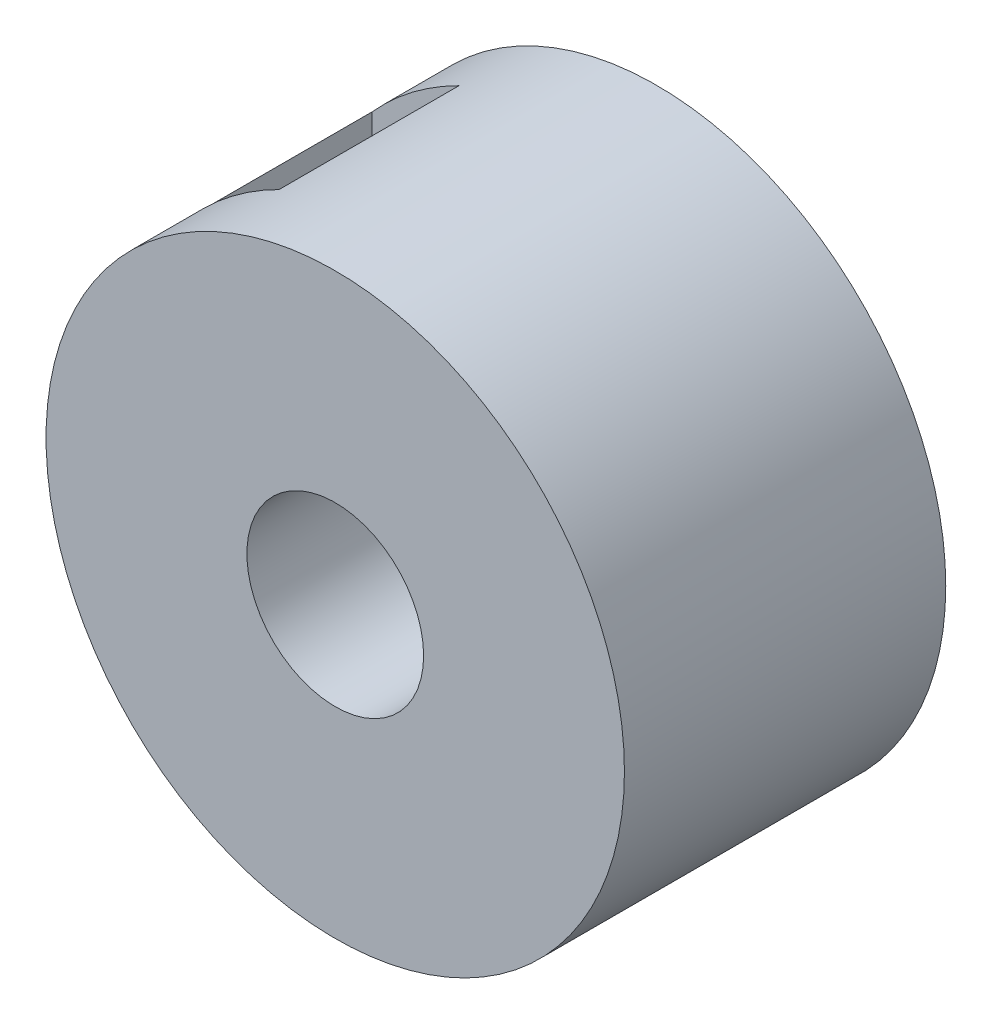
SolidWorks part; units mm, degrees
ref_plane "Front Plane" through (0, 0, 0) normal (0, 0, 1) x (1, 0, 0)
ref_plane "Top Plane" through (0, 0, 0) normal (0, 1, 0) x (1, 0, 0)
ref_plane "Right Plane" through (0, 0, 0) normal (1, 0, 0) x (0, 0, -1)
ref_plane "Plane1" through (0, 0, 5) normal (0, 0, 1) x (1, 0, 0)
sketch "Sketch1" plane through (0, 0, 5) normal (0, 0, 1) x (1, 0, 0)
  line L0 (0.3395, -10.4295) -> (0.4303, -9.9978)
  line L1 (0.4303, -9.9978) -> (0.4135, -9.6065)
  line L2 (0.4135, -9.6065) -> (1.5928, -9.4826)
  line L3 (1.5928, -9.4826) -> (1.6577, -9.8688)
  line L4 (1.6577, -9.8688) -> (1.8363, -10.2722)
  line L5 (1.8363, -10.2722) -> (2.1853, -10.8118)
  line L6 (2.1853, -10.8118) -> (2.7876, -11.48)
  line L7 (2.7876, -11.48) -> (4.0633, -12.5056)
  line L8 (4.0633, -12.5056) -> (4.4925, -10.926)
  line L9 (4.4925, -10.926) -> (4.587, -10.0314)
  line L10 (4.587, -10.0314) -> (4.5522, -9.3898)
  line L11 (4.5522, -9.3898) -> (4.4596, -8.9584)
  line L12 (4.4596, -8.9584) -> (4.2851, -8.6078)
  line L13 (4.2851, -8.6078) -> (5.3121, -8.0149)
  line L14 (5.3121, -8.0149) -> (5.5285, -8.3414)
  line L15 (5.5285, -8.3414) -> (5.8556, -8.6372)
  line L16 (5.8556, -8.6372) -> (6.3939, -8.9882)
  line L17 (6.3939, -8.9882) -> (7.2159, -9.3536)
  line L18 (7.2159, -9.3536) -> (8.7985, -9.7717)
  line L19 (8.7985, -9.7717) -> (8.5481, -8.1541)
  line L20 (8.5481, -8.1541) -> (8.2706, -7.2984)
  line L21 (8.2706, -7.2984) -> (7.9778, -6.7264)
  line L22 (7.9778, -6.7264) -> (7.7178, -6.37)
  line L23 (7.7178, -6.37) -> (7.4157, -6.1207)
  line L24 (7.4157, -6.1207) -> (8.1128, -5.1614)
  line L25 (8.1128, -5.1614) -> (8.4432, -5.3716)
  line L26 (8.4432, -5.3716) -> (8.8625, -5.5088)
  line L27 (8.8625, -5.5088) -> (9.4969, -5.6105)
  line L28 (9.4969, -5.6105) -> (10.3965, -5.61)
  line L29 (10.3965, -5.61) -> (12.0123, -5.3482)
  line L30 (12.0123, -5.3482) -> (11.1257, -3.9723)
  line L31 (11.1257, -3.9723) -> (10.5241, -3.3035)
  line L32 (10.5241, -3.3035) -> (10.024, -2.9)
  line L33 (10.024, -2.9) -> (9.6415, -2.6802)
  line L34 (9.6415, -2.6802) -> (9.2641, -2.5753)
  line L35 (9.2641, -2.5753) -> (9.5107, -1.4154)
  line L36 (9.5107, -1.4154) -> (9.8981, -1.473)
  line L37 (9.8981, -1.473) -> (10.3369, -1.4279)
  line L38 (10.3369, -1.4279) -> (10.9579, -1.2627)
  line L39 (10.9579, -1.2627) -> (11.7795, -0.8963)
  line L40 (11.7795, -0.8963) -> (13.1491, 0)
  line L41 (13.1491, 0) -> (11.7795, 0.8963)
  line L42 (11.7795, 0.8963) -> (10.9579, 1.2627)
  line L43 (10.9579, 1.2627) -> (10.3369, 1.4278)
  line L44 (10.3369, 1.4278) -> (9.8981, 1.473)
  line L45 (9.8981, 1.473) -> (9.5107, 1.4154)
  line L46 (9.5107, 1.4154) -> (9.2641, 2.5753)
  line L47 (9.2641, 2.5753) -> (9.6415, 2.6802)
  line L48 (9.6415, 2.6802) -> (10.024, 2.9)
  line L49 (10.024, 2.9) -> (10.5241, 3.3035)
  line L50 (10.5241, 3.3035) -> (11.1257, 3.9723)
  line L51 (11.1257, 3.9723) -> (12.0123, 5.3482)
  line L52 (12.0123, 5.3482) -> (10.3965, 5.61)
  line L53 (10.3965, 5.61) -> (9.4969, 5.6105)
  line L54 (9.4969, 5.6105) -> (8.8625, 5.5088)
  line L55 (8.8625, 5.5088) -> (8.4432, 5.3716)
  line L56 (8.4432, 5.3716) -> (8.1128, 5.1614)
  line L57 (8.1128, 5.1614) -> (7.4157, 6.1207)
  line L58 (7.4157, 6.1207) -> (7.7178, 6.37)
  line L59 (7.7178, 6.37) -> (7.9778, 6.7264)
  line L60 (7.9778, 6.7264) -> (8.2706, 7.2984)
  line L61 (8.2706, 7.2984) -> (8.5481, 8.1541)
  line L62 (8.5481, 8.1541) -> (8.7985, 9.7717)
  line L63 (8.7985, 9.7717) -> (7.2159, 9.3536)
  line L64 (7.2159, 9.3536) -> (6.3939, 8.9882)
  line L65 (6.3939, 8.9882) -> (5.8556, 8.6372)
  line L66 (5.8556, 8.6372) -> (5.5285, 8.3414)
  line L67 (5.5285, 8.3414) -> (5.3121, 8.0149)
  line L68 (5.3121, 8.0149) -> (4.2851, 8.6078)
  line L69 (4.2851, 8.6078) -> (4.4596, 8.9584)
  line L70 (4.4596, 8.9584) -> (4.5522, 9.3898)
  line L71 (4.5522, 9.3898) -> (4.587, 10.0314)
  line L72 (4.587, 10.0314) -> (4.4925, 10.926)
  line L73 (4.4925, 10.926) -> (4.0633, 12.5056)
  line L74 (4.0633, 12.5056) -> (2.7876, 11.48)
  line L75 (2.7876, 11.48) -> (2.1853, 10.8118)
  line L76 (2.1853, 10.8118) -> (1.8363, 10.2722)
  line L77 (1.8363, 10.2722) -> (1.6577, 9.8688)
  line L78 (1.6577, 9.8688) -> (1.5928, 9.4826)
  line L79 (1.5928, 9.4826) -> (0.4135, 9.6065)
  line L80 (0.4135, 9.6065) -> (0.4303, 9.9978)
  line L81 (0.4303, 9.9978) -> (0.3395, 10.4295)
  line L82 (0.3395, 10.4295) -> (0.1103, 11.0298)
  line L83 (0.1103, 11.0298) -> (-0.3398, 11.8087)
  line L84 (-0.3398, 11.8087) -> (-1.3745, 13.0771)
  line L85 (-1.3745, 13.0771) -> (-2.1227, 11.6213)
  line L86 (-2.1227, 11.6213) -> (-2.4012, 10.7659)
  line L87 (-2.4012, 10.7659) -> (-2.5005, 10.131)
  line L88 (-2.5005, 10.131) -> (-2.4996, 9.6899)
  line L89 (-2.4996, 9.6899) -> (-1.2262, 9.6926)
  line L90 (-1.2262, 9.6926) -> (-3.5296, 8.9442)
  line L91 (-3.5296, 8.9442) -> (-3.6733, 9.3085)
  line L92 (-3.6733, 9.3085) -> (-3.9319, 9.666)
  line L93 (-3.9319, 9.666) -> (-4.3854, 10.1211)
  line L94 (-4.3854, 10.1211) -> (-5.1135, 10.6495)
  line L95 (-5.1135, 10.6495) -> (-6.5745, 11.3875)
  line L96 (-6.5745, 11.3875) -> (-6.666, 9.7532)
  line L97 (-6.666, 9.7532) -> (-6.5724, 8.8585)
  line L98 (-6.5724, 8.8585) -> (-6.405, 8.2381)
  line L99 (-6.405, 8.2381) -> (-6.2247, 7.8354)
  line L100 (-6.2247, 7.8354) -> (-5.9811, 7.5288)
  line L101 (-5.9811, 7.5288) -> (-6.8624, 6.7353)
  line L102 (-6.8624, 6.7353) -> (-7.1419, 7.0097)
  line L103 (-7.1419, 7.0097) -> (-7.5235, 7.231)
  line L104 (-7.5235, 7.231) -> (-8.1229, 7.4624)
  line L105 (-8.1229, 7.4624) -> (-9.003, 7.649)
  line L106 (-9.003, 7.649) -> (-10.6378, 7.7288)
  line L107 (-10.6378, 7.7288) -> (-10.0567, 6.1987)
  line L108 (-10.0567, 6.1987) -> (-9.6073, 5.4194)
  line L109 (-9.6073, 5.4194) -> (-9.202, 4.9207)
  line L110 (-9.202, 4.9207) -> (-8.8735, 4.6262)
  line L111 (-8.8735, 4.6262) -> (-8.5262, 4.4452)
  line L112 (-8.5262, 4.4452) -> (-9.0086, 3.3618)
  line L113 (-9.0086, 3.3618) -> (-9.3755, 3.4988)
  line L114 (-9.3755, 3.4988) -> (-9.8141, 3.5458)
  line L115 (-9.8141, 3.5458) -> (-10.4559, 3.5133)
  line L116 (-10.4559, 3.5133) -> (-11.3357, 3.3259)
  line L117 (-11.3357, 3.3259) -> (-12.8618, 2.7339)
  line L118 (-12.8618, 2.7339) -> (-11.7085, 1.5723)
  line L119 (-11.7085, 1.5723) -> (-10.9809, 1.0432)
  line L120 (-10.9809, 1.0432) -> (-10.4079, 0.7525)
  line L121 (-10.4079, 0.7525) -> (-9.9881, 0.6171)
  line L122 (-9.9881, 0.6171) -> (-9.5971, 0.5929)
  line L123 (-9.5971, 0.5929) -> (-9.5971, -0.5929)
  line L124 (-9.5971, -0.5929) -> (-9.9881, -0.6171)
  line L125 (-9.9881, -0.6171) -> (-10.4079, -0.7525)
  line L126 (-10.4079, -0.7525) -> (-10.9809, -1.0432)
  line L127 (-10.9809, -1.0432) -> (-11.7085, -1.5723)
  line L128 (-11.7085, -1.5723) -> (-12.8618, -2.7339)
  line L129 (-12.8618, -2.7339) -> (-11.3357, -3.3259)
  line L130 (-11.3357, -3.3259) -> (-10.4559, -3.5133)
  line L131 (-10.4559, -3.5133) -> (-9.8141, -3.5458)
  line L132 (-9.8141, -3.5458) -> (-9.3755, -3.4988)
  line L133 (-9.3755, -3.4988) -> (-9.0086, -3.3618)
  line L134 (-9.0086, -3.3618) -> (-8.5262, -4.4452)
  line L135 (-8.5262, -4.4452) -> (-8.8735, -4.6262)
  line L136 (-8.8735, -4.6262) -> (-9.202, -4.9207)
  line L137 (-9.202, -4.9207) -> (-9.6073, -5.4194)
  line L138 (-9.6073, -5.4194) -> (-10.0567, -6.1987)
  line L139 (-10.0567, -6.1987) -> (-10.6378, -7.7288)
  line L140 (-10.6378, -7.7288) -> (-9.003, -7.649)
  line L141 (-9.003, -7.649) -> (-8.1229, -7.4624)
  line L142 (-8.1229, -7.4624) -> (-7.5235, -7.231)
  line L143 (-7.5235, -7.231) -> (-7.1419, -7.0097)
  line L144 (-7.1419, -7.0097) -> (-6.8624, -6.7353)
  line L145 (-6.8624, -6.7353) -> (-5.9811, -7.5288)
  line L146 (-5.9811, -7.5288) -> (-6.2247, -7.8354)
  line L147 (-6.2247, -7.8354) -> (-6.405, -8.2381)
  line L148 (-6.405, -8.2381) -> (-6.5724, -8.8585)
  line L149 (-6.5724, -8.8585) -> (-6.666, -9.7532)
  line L150 (-6.666, -9.7532) -> (-6.5745, -11.3875)
  line L151 (-6.5745, -11.3875) -> (-5.1135, -10.6495)
  line L152 (-5.1135, -10.6495) -> (-4.3854, -10.1211)
  line L153 (-4.3854, -10.1211) -> (-3.9319, -9.666)
  line L154 (-3.9319, -9.666) -> (-3.6733, -9.3085)
  line L155 (-3.6733, -9.3085) -> (-3.5296, -8.9442)
  line L156 (-3.5296, -8.9442) -> (-1.2262, -9.6926)
  line L157 (-1.2262, -9.6926) -> (-2.4996, -9.6899)
  line L158 (-2.4996, -9.6899) -> (-2.5005, -10.131)
  line L159 (-2.5005, -10.131) -> (-2.4012, -10.7659)
  line L160 (-2.4012, -10.7659) -> (-2.1227, -11.6213)
  line L161 (-2.1227, -11.6213) -> (-1.3745, -13.0771)
  line L162 (-1.3745, -13.0771) -> (-0.3398, -11.8087)
  line L163 (-0.3398, -11.8087) -> (0.1103, -11.0298)
  line L164 (0.1103, -11.0298) -> (0.3395, -10.4295)
extrude "Boss-Extrude1" add sketch "Sketch1" against normal blind 5
sketch "Sketch2" plane through (0, 0, 5) normal (0, 0, 1) x (1, 0, 0)
  line L0 (3.75, -6.4952) -> (1.9411, -7.2444)
  line L1 (1.9411, -7.2444) -> (0, -7.5)
  line L2 (0, -7.5) -> (-1.9411, -7.2444)
  line L3 (-1.9411, -7.2444) -> (-3.75, -6.4952)
  line L4 (-3.75, -6.4952) -> (-5.3033, -5.3033)
  line L5 (-5.3033, -5.3033) -> (-6.4952, -3.75)
  line L6 (-6.4952, -3.75) -> (-7.2444, -1.9411)
  line L7 (-7.2444, -1.9411) -> (-7.5, 0)
  line L8 (-7.5, 0) -> (-7.2444, 1.9411)
  line L9 (-7.2444, 1.9411) -> (-6.4952, 3.75)
  line L10 (-6.4952, 3.75) -> (-5.3033, 5.3033)
  line L11 (-5.3033, 5.3033) -> (-3.75, 6.4952)
  line L12 (-3.75, 6.4952) -> (-1.9411, 7.2444)
  line L13 (-1.9411, 7.2444) -> (0, 7.5)
  line L14 (0, 7.5) -> (1.9411, 7.2444)
  line L15 (1.9411, 7.2444) -> (3.75, 6.4952)
  line L16 (3.75, 6.4952) -> (5.3033, 5.3033)
  line L17 (5.3033, 5.3033) -> (6.4952, 3.75)
  line L18 (6.4952, 3.75) -> (7.2444, 1.9411)
  line L19 (7.2444, 1.9411) -> (7.5, 0)
  line L20 (7.5, 0) -> (7.2444, -1.9411)
  line L21 (7.2444, -1.9411) -> (6.4952, -3.75)
  line L22 (6.4952, -3.75) -> (5.3033, -5.3033)
  line L23 (5.3033, -5.3033) -> (3.75, -6.4952)
extrude "Boss-Extrude2" add sketch "Sketch2" along normal blind 10
sketch "Sketch3" plane through (0, 0, 0) normal (0, 0, -1) x (-1, 0, 0)
  line L0 (0, 2.5) -> (-1.7678, 1.7678)
  line L1 (-1.7678, 1.7678) -> (-2.5, 0)
  line L2 (-2.5, 0) -> (-1.7678, -1.7678)
  line L3 (-1.7678, -1.7678) -> (0, -2.5)
  line L4 (0, -2.5) -> (1.7678, -1.7678)
  line L5 (1.7678, -1.7678) -> (2.5, 0)
  line L6 (2.5, 0) -> (1.7678, 1.7678)
  line L7 (1.7678, 1.7678) -> (0, 2.5)
extrude "Cut-Extrude1" cut sketch "Sketch3" against normal through all
draft "Draft1" type of draft neutral plane draft angle 75.657 faces to draft 1 face at (-1.8629, -9.6913, 2.5) neutral plane through (-2.4996, -9.6899, 0) neutral plane normal (-1, 0.0021, 0) parameters "D1"=75.657
draft "Draft2" type of draft neutral plane draft angle 75.657 faces to draft 1 face at (-1.8629, 9.6913, 2.5) neutral plane through (-2.5005, 10.131, 0) neutral plane normal (-1, -0.0021, 0) parameters "D1"=75.657
chamfer "Chamfer1" distance 0.4803 angle 56.786 1 edges at (-1.3745, -13.0771, 2.5)
chamfer "Chamfer2" distance 0.0739 angle 6.156 1 edges at (8.4432, 5.3716, 2.5)
chamfer "Chamfer3" distance 0.0739 angle 6.154 1 edges at (0.4303, -9.9978, 2.5)
chamfer "Chamfer4" distance 0.4803 angle 56.796 1 edges at (8.7985, 9.7717, 2.5)
chamfer "Chamfer5" distance 0.0556 angle 8.192 1 edges at (1.6577, -9.8688, 2.5)
chamfer "Chamfer6" distance 0.074 angle 6.147 1 edges at (5.5285, 8.3414, 2.5)
chamfer "Chamfer7" distance 0.4802 angle 56.804 1 edges at (4.0633, -12.5056, 2.5)
chamfer "Chamfer8" distance 0.074 angle 6.151 1 edges at (4.4596, 8.9584, 2.5)
chamfer "Chamfer9" distance 0.4802 angle 56.798 1 edges at (13.1491, 0, 2.5)
chamfer "Chamfer10" distance 0.0739 angle 6.152 1 edges at (1.6577, 9.8688, 2.5)
chamfer "Chamfer11" distance 0.074 angle 6.15 2 edges at (-7.1419, 7.0097, 2.5) (-7.1419, -7.0097, 2.5)
chamfer "Chamfer12" distance 0.0556 angle 8.194 2 edges at (-2.4996, -9.6899, 2.5) (-2.4996, 9.6899, 2.5)
chamfer "Chamfer13" distance 0.0556 angle 8.193 1 edges at (9.8981, -1.473, 2.5)
chamfer "Chamfer14" distance 0.0556 angle 8.188 1 edges at (0.4303, 9.9978, 2.5)
chamfer "Chamfer15" distance 0.0556 angle 8.188 2 edges at (-6.2247, 7.8354, 2.5) (-6.2247, -7.8354, 2.5)
chamfer "Chamfer16" distance 0.4802 angle 56.802 2 edges at (-10.6378, 7.7288, 2.5) (-10.6378, -7.7288, 2.5)
chamfer "Chamfer17" distance 0.0556 angle 8.189 1 edges at (8.4432, -5.3716, 2.5)
chamfer "Chamfer18" distance 0.0739 angle 6.154 2 edges at (-8.8735, -4.6262, 2.5) (-8.8735, 4.6262, 2.5)
chamfer "Chamfer19" distance 0.0739 angle 6.15 2 edges at (9.6415, -2.6802, 2.5) (9.6415, 2.6802, 2.5)
chamfer "Chamfer20" distance 0.0739 angle 6.153 2 edges at (-9.3755, 3.4988, 2.5) (-9.3755, -3.4988, 2.5)
chamfer "Chamfer21" distance 0.0556 angle 8.192 1 edges at (-9.9881, 0.6171, 2.5)
chamfer "Chamfer22" distance 0.4803 angle 56.793 2 edges at (-12.8618, -2.7339, 2.5) (-12.8618, 2.7339, 2.5)
chamfer "Chamfer23" distance 0.4802 angle 56.806 1 edges at (-1.3745, 13.0771, 2.5)
chamfer "Chamfer24" distance 0.0557 angle 8.187 1 edges at (-3.6733, -9.3085, 2.5)
chamfer "Chamfer25" distance 0.0739 angle 6.151 1 edges at (9.8981, 1.473, 2.5)
chamfer "Chamfer26" distance 0.4803 angle 56.794 1 edges at (12.0123, 5.3482, 2.5)
chamfer "Chamfer27" distance 0.0556 angle 8.197 1 edges at (5.5285, -8.3414, 2.5)
chamfer "Chamfer28" distance 0.4802 angle 56.798 1 edges at (8.7985, -9.7717, 2.5)
chamfer "Chamfer29" distance 0.4802 angle 56.801 1 edges at (12.0123, -5.3482, 2.5)
chamfer "Chamfer30" distance 0.074 angle 6.152 1 edges at (-9.9881, -0.6171, 2.5)
chamfer "Chamfer31" distance 0.4803 angle 56.79 1 edges at (4.0633, 12.5056, 2.5)
chamfer "Chamfer32" distance 0.0739 angle 6.158 1 edges at (-3.6733, 9.3085, 2.5)
chamfer "Chamfer33" distance 0.0556 angle 8.188 2 edges at (7.7178, -6.37, 2.5) (7.7178, 6.37, 2.5)
chamfer "Chamfer34" distance 0.4803 angle 56.795 2 edges at (-6.5745, -11.3875, 2.5) (-6.5745, 11.3875, 2.5)
chamfer "Chamfer35" distance 0.0556 angle 8.194 1 edges at (4.4596, -8.9584, 2.5)
sketch "Sketch8" plane through (0, 0, 15) normal (0, 0, 1) x (1, 0, 0)
  circle A0 centre (0, 0) radius 7
  circle A1 centre (0, 0) radius 9
  dimension "D1" = 18
  dimension "D2" = 14
extrude "Boss-Extrude3" add sketch "Sketch8" against normal up to surface (10 mm away) up to face at (-0.0003, -0.0002, 5)
sketch "Sketch4" plane through (0, 0, 15) normal (0, 0, 1) x (1, 0, 0)
  circle A0 centre (0, 0) radius 2.75
  dimension "D1" = 5.5
extrude "5.5mmShaftHole" cut sketch "Sketch4" against normal up to surface (15 mm away) up to face at (0, 0, 0)
sketch "Sketch5" plane through (0, 0, 0) normal (0, 1, 0) x (1, 0, 0)
  line L1 (-6.7, -12.75) -> (-4, -12.75)
  line L2 (-6.7, -12.75) -> (-6.7, -7.15)
  line L3 (-6.7, -7.15) -> (-4, -7.15)
  line L4 (-4, -12.75) -> (-4, -7.15)
  line L5 (-6.7, -12.75) -> (-4, -7.15) construction
  line L6 (-6.7, -7.15) -> (-4, -12.75) construction
  line L8 (-9, -15) -> (9, -15) construction
  point P4 (-5.35, -9.95)
  dimension "D1" = 5.6
  dimension "D2" = 2.7
  dimension "D3" = 2.25
  dimension "D4" = 4
extrude "NutPlace" cut sketch "Sketch5" against normal blind 3.3 and the other way through all
sketch "Sketch6" plane through (0, 0, 0) normal (1, 0, 0) x (0, 0, -1)
  line L0 (-15, 2.75) -> (-15, -2.75) construction
  circle A0 centre (-10, 0) radius 1.6
  dimension "D1" = 5
  dimension "D2" = 3.2
extrude "3.3mmScrewHole for m3" cut sketch "Sketch6" against normal through all
ref_plane "Plane4" through (-9, 0, 0) normal (-1, 0, 0) x (0, 0, 1)
sketch "Sketch9" plane through (-9, 0, 0) normal (-1, 0, 0) x (0, 0, 1)
  circle A0 centre (10, 0) radius 2.75
  dimension "D1" = 5.5
extrude "Cut-Extrude2" cut sketch "Sketch9" against normal blind 0.45
ref_plane "Plane5" through (0, 0, 5) normal (0, 0, 1) x (1, 0, 0)
other "SurfaceCut1"
